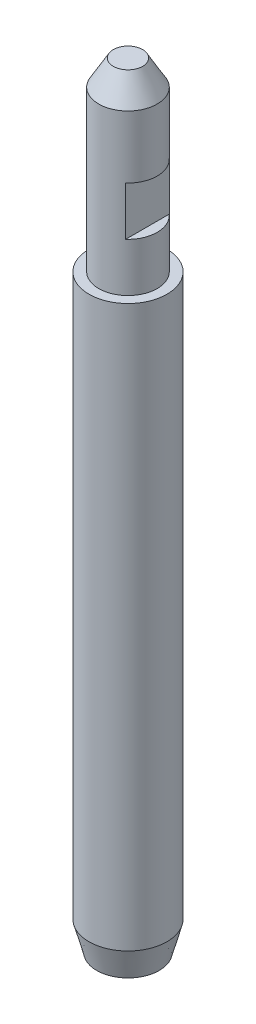
SolidWorks part; units mm, degrees
ref_plane "Face" through (0, 0, 0) normal (0, 0, 1) x (1, 0, 0)
ref_plane "Dessus" through (0, 0, 0) normal (0, 1, 0) x (1, 0, 0)
ref_plane "Droite" through (0, 0, 0) normal (1, 0, 0) x (0, 0, -1)
ref_plane "Plan2" through (0, 72.69, 0) normal (0, 1, 0) x (-1, 0, 0)
sketch "Esquisse1" plane through (0, 0, 0) normal (0, 0, 1) x (1, 0, 0)
  line L0 (-101, 106.9729) -> (-101, 18.329) construction
  line L1 (-101, 128.7543) -> (-101, 102) construction
  line L2 (-101, 30) -> (-104.2081, 30)
  line L3 (-96.75, 30) -> (-105.25, 30) construction
  line L4 (-105, 32.9554) -> (-105, 90.5)
  line L5 (-104, 90.5) -> (-105, 90.5)
  line L6 (-104, 90.5) -> (-98, 90.5) construction
  line L7 (-104, 90.5) -> (-104, 106.9019)
  line L8 (-102.5, 109.5) -> (-104, 106.9019)
  line L9 (-105, 32.9554) -> (-104.2081, 30)
  line L10 (-101, 109.5) -> (-101, 30)
  line L12 (-102.5, 109.5) -> (-101, 109.5)
  dimension "D1" = 120
  dimension "D2" = 4
  dimension "D3" = 15
revolve "Révolution1" add sketch "Esquisse1" angle 360 about L0
sketch "Esquisse3" plane through (0, 30, 0) normal (0, -1, 0) x (1, 0, 0)
  circle A0 centre (-101, 0) radius 1.6
extrude "Enlèv. mat.-Extru.1" cut sketch "Esquisse3" against normal blind 10
ref_plane "Plan1" through (0, 29.5, 0) normal (0, 1, 0) x (-1, 0, 0)
sketch "Esquisse4" plane through (0, 29.5, 0) normal (0, 1, 0) x (-1, 0, 0)
  line L0 (103.7, -3.6133) -> (103.7, 3.6309)
  line L1 (101, -2.6525) -> (101, 2.6701) construction
  line L2 (103.7, -3.6133) -> (105.8293, 0)
  line L3 (105.8293, 0) -> (103.7, 3.6309)
  dimension "D1" = 2.7
extrude "Enlèv. mat.-Extru.2" [suppressed] cut sketch "Esquisse4" along normal blind 11
sketch "Esquisse5" plane through (0, 0, 0) normal (0, 0, 1) x (1, 0, 0)
  line L0 (-101, 106.8099) -> (-101, 70.3117) construction
  line L1 (-104.9553, 100.5) -> (-103, 100.5)
  line L2 (-104.9553, 100.5) -> (-104.9553, 95.5)
  line L3 (-104.9553, 95.5) -> (-103, 95.5)
  line L4 (-103, 100.5) -> (-103, 95.5)
  line L5 (-101, 90.5) -> (-101, 106.9019) construction
  line L6 (-97.0447, 100.5) -> (-99, 100.5)
  line L7 (-97.0447, 100.5) -> (-97.0447, 95.5)
  line L8 (-97.0447, 95.5) -> (-99, 95.5)
  line L9 (-99, 100.5) -> (-99, 95.5)
  dimension "D1" = 2
  dimension "D2" = 5
extrude "Enlèv. mat.-Extru.3" cut sketch "Esquisse5" against normal mid plane 11
